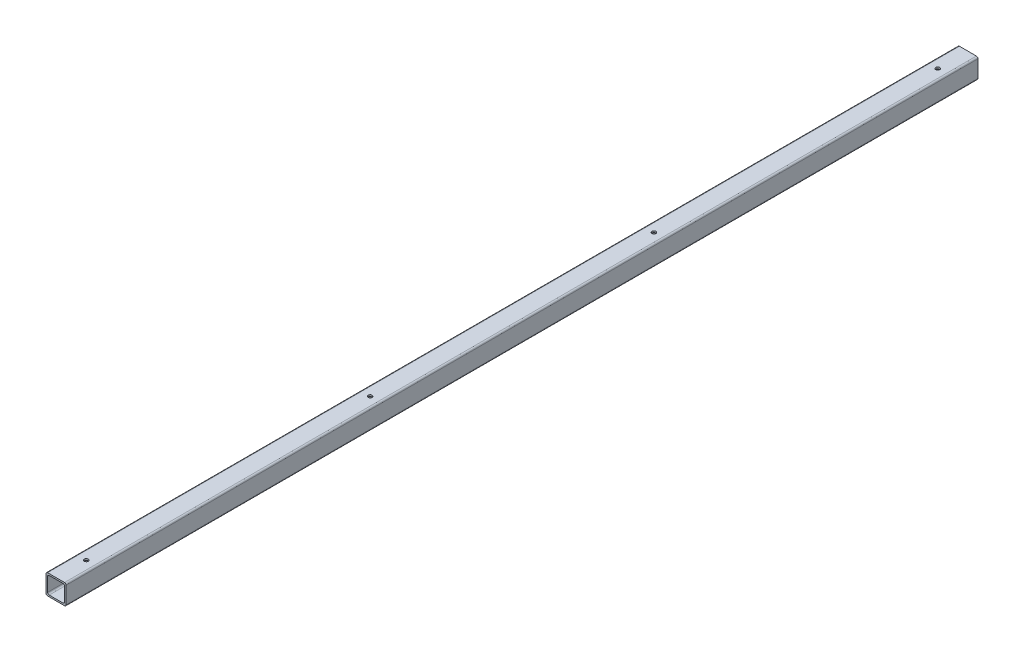
SolidWorks part; units mm, degrees
material "A500"
ref_plane "Alzado" through (0, 0, 0) normal (0, 0, 1) x (1, 0, 0)
ref_plane "Planta" through (0, 0, 0) normal (0, 1, 0) x (1, 0, 0)
ref_plane "Vista lateral" through (0, 0, 0) normal (1, 0, 0) x (0, 0, -1)
sketch "Croquis1" plane through (0, 0, 0) normal (0, 0, 1) x (1, 0, 0)
  line L1 (12.7, 12.7) -> (-12.7, 12.7)
  line L2 (12.7, 12.7) -> (12.7, -12.7)
  line L3 (12.7, -12.7) -> (-12.7, -12.7)
  line L4 (-12.7, 12.7) -> (-12.7, -12.7)
  line L5 (12.7, 12.7) -> (-12.7, -12.7) construction
  line L6 (12.7, -12.7) -> (-12.7, 12.7) construction
  line L7 (10.7, -10.7) -> (-10.7, -10.7)
  line L8 (10.7, -10.7) -> (10.7, 10.7)
  line L9 (10.7, 10.7) -> (-10.7, 10.7)
  line L10 (-10.7, -10.7) -> (-10.7, 10.7)
  line L11 (10.7, -10.7) -> (-10.7, 10.7) construction
  line L12 (10.7, 10.7) -> (-10.7, -10.7) construction
  point P0 (0, 0)
  point P6 (0, 0)
  dimension "D1" = 25.4
  dimension "D2" = 25.4
  dimension "D3" = 2
extrude "Saliente-Extruir1" add sketch "Croquis1" along normal blind 1150
fillet "Redondeo1" radius 2 8 edges at (-10.7, -10.7, 575) (-10.7, 10.7, 575) (10.7, 10.7, 575) (10.7, -10.7, 575) (12.7, -12.7, 575) (-12.7, -12.7, 575) (-12.7, 12.7, 575) (12.7, 12.7, 575)
sketch "Croquis2" plane through (0, 12.7, 0) normal (0, 1, 0) x (1, 0, 0)
  line L0 (0, -1150) -> (0, -1111.1443) construction
  line L1 (10.7, -1150) -> (-10.7, -1150) construction
  circle A0 centre (0, -1111.9) radius 2.5
  dimension "D1" = 5
  dimension "D2" = 38.1
extrude "Cortar-Extruir1" cut sketch "Croquis2" against normal blind 10
pattern_linear "MatrizL1" count 4 spacing 357.9333 along (0, 0, -1) of "Cortar-Extruir1"
sketch "Croquis3" plane through (0, -12.7, 0) normal (0, -1, 0) x (1, 0, 0)
  line L0 (0, 1150) -> (0, 1111.9) construction
  line L1 (-10.7, 1150) -> (10.7, 1150) construction
  circle A0 centre (0, 1111.9) radius 6
  dimension "D1" = 12
  dimension "D2" = 38.1
extrude "Cortar-Extruir2" cut sketch "Croquis3" against normal blind 10
pattern_linear "MatrizL2" count 4 spacing 357.9333 along (0, 0, -1) of "Cortar-Extruir2"
